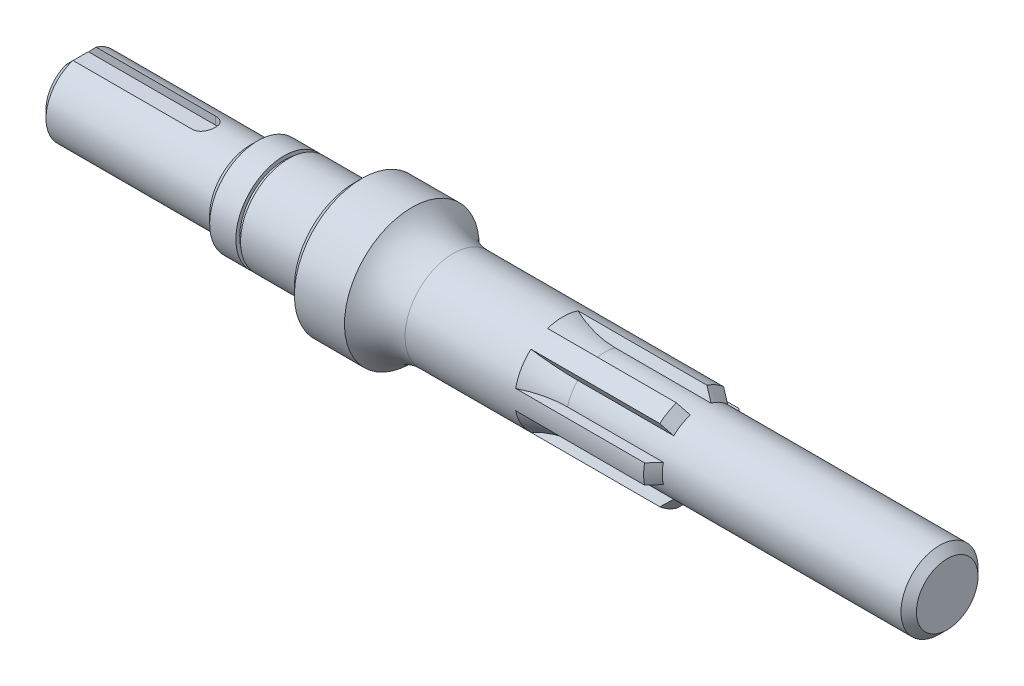
SolidWorks part; units mm, degrees
ref_plane "前视基准面" through (0, 0, 0) normal (0, 0, 1) x (1, 0, 0)
ref_plane "上视基准面" through (0, 0, 0) normal (0, 1, 0) x (1, 0, 0)
ref_plane "右视基准面" through (0, 0, 0) normal (1, 0, 0) x (0, 0, -1)
sketch "草图1" plane through (0, 0, 0) normal (0, 0, 1) x (1, 0, 0)
  line L0 (0, 0) -> (-154, 0) construction
  line L1 (0, 0) -> (0, 10)
  line L2 (0, 10) -> (-88.9028, 10)
  line L3 (-99.8, 12.5) -> (-128.2762, 12.5)
  line L4 (0, -55) -> (0, 55) construction
  line L5 (-139, 17.5) -> (-154, 17.5)
  line L6 (-154, 17.5) -> (-154, 0)
  line L7 (0, 0) -> (-154, 0)
  arc A0 (-88.9028, 10) -> (-99.8, 12.5) centre (-88.9028, 35) cw
  arc A1 (-128.2762, 12.5) -> (-139, 17.5) centre (-128.2762, 26.5) cw
  point P12 (-188.5122, 0)
  point P14 (-158.1218, 37.3711)
  dimension "D1" = 14
  dimension "D5" = 25
  dimension "D2" = 35
  dimension "D3" = 25
  dimension "D4" = 20
  dimension "D6" = 99.8
  dimension "D7" = 15
  dimension "D8" = 154
revolve "旋转1" add sketch "草图1" angle 360 about L0
sketch "草图2" plane through (-154, 0, 0) normal (-1, 0, 0) x (0, 0, 1)
  circle A0 centre (0, 0) radius 12.5
  dimension "D1" = 25
extrude "凸台-拉伸1" add sketch "草图2" along normal blind 27
sketch "草图3" plane through (-181, 0, 0) normal (-1, 0, 0) x (0, 0, 1)
  circle A0 centre (0, 0) radius 10
  dimension "D1" = 20
extrude "凸台-拉伸2" add sketch "草图3" along normal blind 45
sketch "草图5" plane through (-181, 0, 0) normal (-1, 0, 0) x (0, 0, 1)
  circle A0 centre (0, 0) radius 11.5
  dimension "D1" = 23
extrude "切除-拉伸1" cut sketch "草图5" against normal blind 1.2 from offset 8.8 flip side to cut offset against normal yes
sketch "草图7" plane through (0, 0, 0) normal (0, 1, 0) x (1, 0, 0)
  line L0 (-226, 0) -> (-193, 0) construction
  line L1 (-226, 10) -> (-226, -10) construction
  line L2 (-19.25, 0) -> (19.25, 0) construction
  line L3 (-226, 3) -> (-193, 3)
  line L4 (-226, -3) -> (-193, -3)
  arc A0 (-226, 3) -> (-226, -3) centre (-226, 0) ccw
  arc A1 (-193, -3) -> (-193, 3) centre (-193, 0) ccw
  point P7 (-209.5, 0)
  dimension "D2" = 3
  dimension "D1" = 33
extrude "切除-拉伸2" cut sketch "草图7" along normal through all from offset 7.5
sketch "草图8" plane through (0, 0, 0) normal (1, 0, 0) x (0, 0, -1)
  line L0 (12.2474, 2.5) -> (9.6825, 2.5)
  line L1 (12.2474, -2.5) -> (9.6825, -2.5)
  line L2 (19.25, 0) -> (-19.25, 0) construction
  circle A0 centre (0, 0) radius 12.5 construction
  arc A1 (12.2474, -2.5) -> (12.2474, 2.5) centre (0, 0) ccw
  circle A3 centre (0, 0) radius 10
  arc A4 (9.6825, -2.5) -> (9.6825, 2.5) centre (0, 0) ccw
  dimension "D2" = 5
  dimension "D3" = 2.5
  dimension "D1" = 0
extrude "凸台-拉伸3" add sketch "草图8" against normal up to next from offset 64 offset against normal yes
pattern_circular "阵列(圆周)1" count 6 over 360 about axis through (0, 0, 0) along (1, 0, 0) of "凸台-拉伸3"
sketch "草图9" plane through (0, 0, 0) normal (0, 1, 0) x (1, 0, 0)
  line L0 (-64, 10) -> (-66.3296, 12.5)
  line L1 (-64, 12.5) -> (-128.2762, 12.5) construction
  line L2 (0, 0) -> (27.205, 0) construction
  line L3 (-19.25, 0) -> (19.25, 0) construction
  line L4 (-64, 10) -> (-64, 12.5)
  line L5 (-64, 12.5) -> (-66.3296, 12.5)
  point P13 (-64.0204, 12.5)
  point P14 (-64, 9.9157)
revolve "切除-旋转1" cut sketch "草图9" angle 360 about L2
chamfer "倒角1" distance 2 angle 45 4 edges at (-226, -10, 0) (-181, -12.5, 0) (-154, 17.5, 0) (0, 10, 0)
